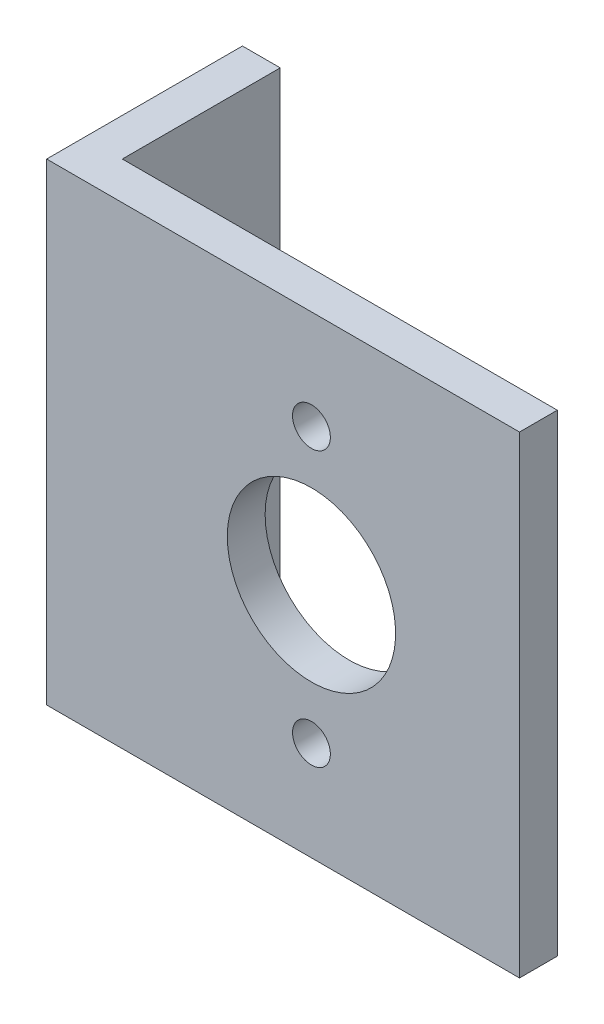
SolidWorks part; units mm, degrees
ref_plane "Спереди" through (0, 0, 0) normal (0, 0, 1) x (1, 0, 0)
ref_plane "Сверху" through (0, 0, 0) normal (0, 1, 0) x (1, 0, 0)
ref_plane "Справа" through (0, 0, 0) normal (1, 0, 0) x (0, 0, -1)
sketch "Эскиз1" plane through (0, 0, 0) normal (0, 1, 0) x (1, 0, 0)
  line L1 (0, 0) -> (50, 0)
  line L2 (0, 0) -> (0, 4)
  line L3 (4, 4) -> (50, 4)
  line L4 (50, 0) -> (50, 4)
  line L6 (0, 4) -> (0, 20.7)
  line L7 (0, 20.7) -> (4, 20.7)
  line L8 (4, 4) -> (4, 20.7)
  dimension "D1" = 50
  dimension "D2" = 4
  dimension "D3" = 20.7
  dimension "D4" = 4
extrude "Бобышка-Вытянуть1" add sketch "Эскиз1" along normal blind 50
sketch "Эскиз2" plane through (0, 0, 0) normal (-1, 0, 0) x (0, 0, 1)
  line L0 (-10, 50) -> (-10, 0) construction
  line L1 (-20.7, 50) -> (0, 50) construction
  line L3 (0, 50) -> (0, 0) construction
  circle A0 centre (-10, 35) radius 3
  circle A1 centre (-10, 15) radius 3
  dimension "D2" = 6
  dimension "D3" = 6
  dimension "D1" = 10
  dimension "D4" = 15
  dimension "D5" = 20
extrude "Вырез-Вытянуть1" cut sketch "Эскиз2" against normal blind 4
sketch "Эскиз3" plane through (0, 0, -4) normal (0, 0, -1) x (-1, 0, 0)
  line L0 (-28, 50) -> (-28, 0) construction
  line L1 (-50, 50) -> (-4, 50) construction
  line L2 (-4, 50) -> (-4, 0) construction
  circle A0 centre (-28, 25) radius 8.9
  circle A1 centre (-28, 39.5) radius 2
  circle A2 centre (-28, 10.5) radius 2
  dimension "D2" = 17.8
  dimension "D4" = 4
  dimension "D5" = 4
  dimension "D1" = 24
  dimension "D3" = 25
  dimension "D6" = 29
  dimension "D7" = 14.5
extrude "Вырез-Вытянуть2" cut sketch "Эскиз3" against normal blind 4
